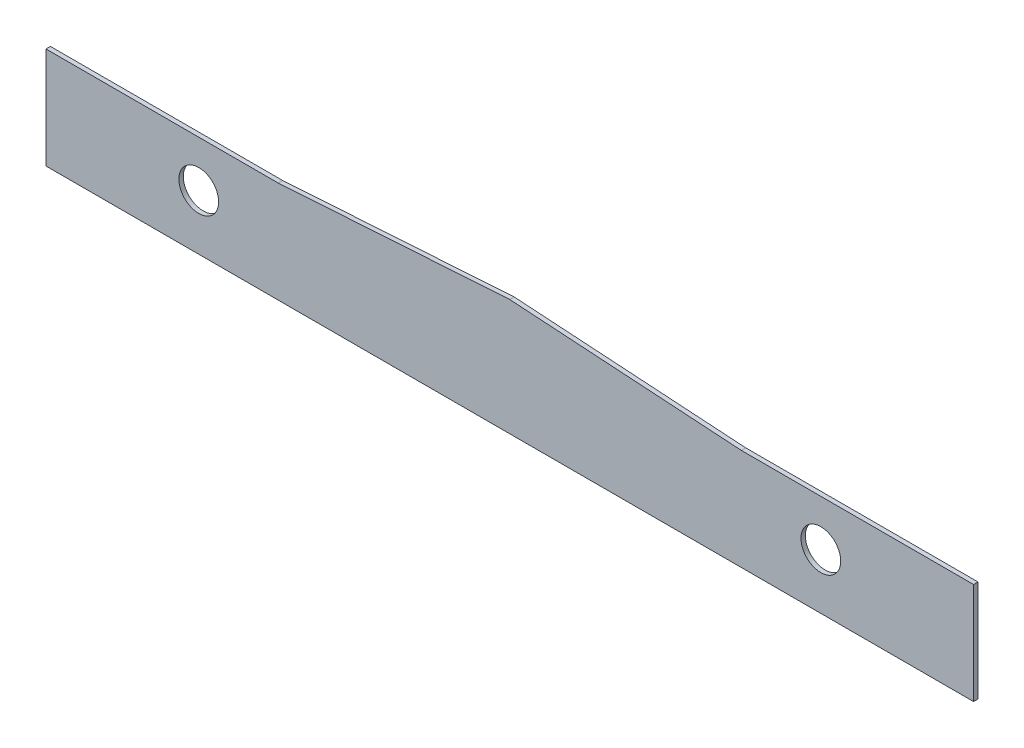
SolidWorks part; units mm, degrees
ref_plane "Piano frontale" through (0, 0, 0) normal (0, 0, 1) x (1, 0, 0)
ref_plane "Piano superiore" through (0, 0, 0) normal (0, 1, 0) x (1, 0, 0)
ref_plane "Piano destro" through (0, 0, 0) normal (1, 0, 0) x (0, 0, -1)
sketch "Schizzo1" plane through (0, 0, 0) normal (0, 0, 1) x (1, 0, 0)
  line L1 (210, -22.96) -> (-210, -22.96)
  line L2 (210, -22.96) -> (210, 22.96)
  line L3 (210, 22.96) -> (-210, 22.96)
  line L4 (-210, -22.96) -> (-210, 22.96)
  line L5 (210, -22.96) -> (-210, 22.96) construction
  line L6 (210, 22.96) -> (-210, -22.96) construction
  point P0 (0, 0)
  point P6 (0, 0)
  dimension "D1" = 45.92
  dimension "D2" = 420
extrude "PiastraBase" add sketch "Schizzo1" along normal blind 2
sketch "Schizzo2" plane through (0, 0, 2) normal (0, 0, 1) x (1, 0, 0)
  circle A0 centre (-140.8333, 2.04) radius 9
  point P2 (0, 0)
  dimension "D1" = 18
extrude "ForoTuboMotore" cut sketch "Schizzo2" against normal through all
mirror "Specchia1" about plane through (0, 0, 0) normal (1, 0, 0) of "ForoTuboMotore"
sketch "Schizzo4" plane through (0, 0, 2) normal (0, 0, 1) x (1, 0, 0)
  line L3 (104.8447, 22.96) -> (0, 29.7092)
  line L4 (210, 22.96) -> (-210, 22.96) construction
  line L5 (105, 22.95) -> (0, 29.7092) construction
  line L6 (0, 29.7092) -> (0, 22.96)
  line L13 (0, 22.96) -> (104.8447, 22.96)
extrude "Estrusione-Estrusione1" add sketch "Schizzo4" against normal up to surface (2 mm away) up to face at (131.8333, 2.04, 0)
mirror "Specchia2" about plane through (0, 0, 0) normal (1, 0, 0) of "Estrusione-Estrusione1"
